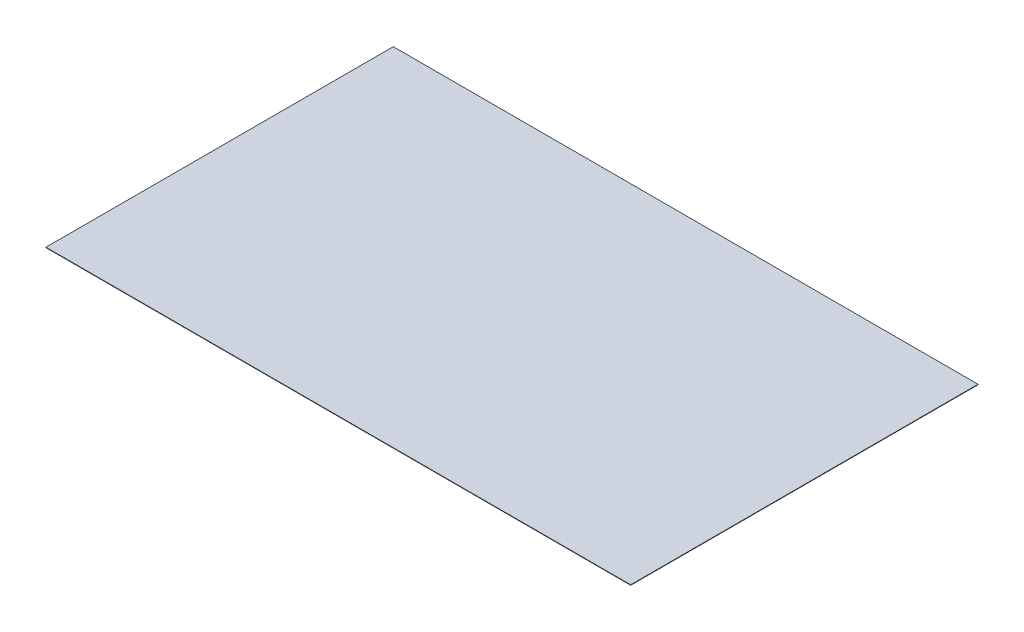
SolidWorks part; units mm, degrees
ref_plane "Front Plane" through (0, 0, 0) normal (0, 0, 1) x (1, 0, 0)
ref_plane "Top Plane" through (0, 0, 0) normal (0, 1, 0) x (1, 0, 0)
ref_plane "Right Plane" through (0, 0, 0) normal (1, 0, 0) x (0, 0, -1)
other "Configuration Table"
sketch "Sketch1" plane through (0, 0, 0) normal (0, 0, 1) x (1, 0, 0)
  line L1 (61.5, 1669) -> (1338.5, 1669)
  line L2 (61.5, 1669) -> (61.5, 1670)
  line L3 (61.5, 1670) -> (1338.5, 1670)
  line L4 (1338.5, 1669) -> (1338.5, 1670)
extrude "STORE_teknik_taban_1" add sketch "Sketch1" against normal blind 758.5 separate body
